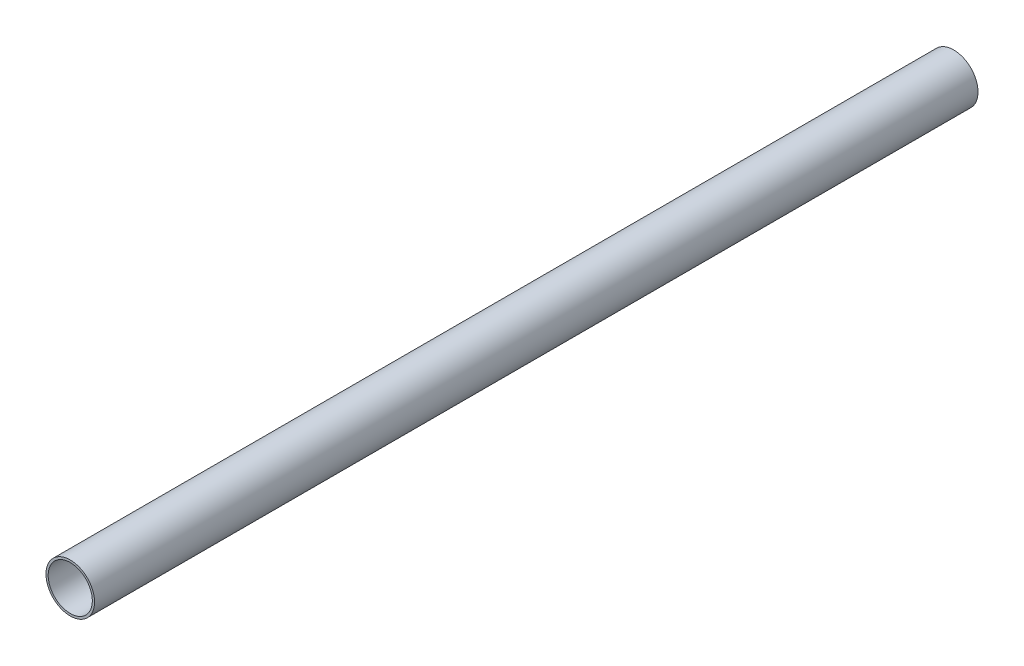
SolidWorks part; units mm, degrees
ref_plane "前视基准面" through (0, 0, 0) normal (0, 0, 1) x (1, 0, 0)
ref_plane "上视基准面" through (0, 0, 0) normal (0, 1, 0) x (1, 0, 0)
ref_plane "右视基准面" through (0, 0, 0) normal (1, 0, 0) x (0, 0, -1)
sketch "草图1" plane through (0, 0, 0) normal (0, 0, 1) x (1, 0, 0)
  circle A0 centre (0, 0) radius 55
  dimension "D1" = 110
extrude "凸台-拉伸1" add sketch "草图1" along normal blind 2000
sketch "草图2" plane through (0, 0, 2000) normal (0, 0, 1) x (1, 0, 0)
  circle A0 centre (0, 0) radius 50
  dimension "D1" = 100
extrude "切除-拉伸1" cut sketch "草图2" against normal blind 1900
scale "缩放比例1" scale about origin uniform scaling yes scale factor 0.345
